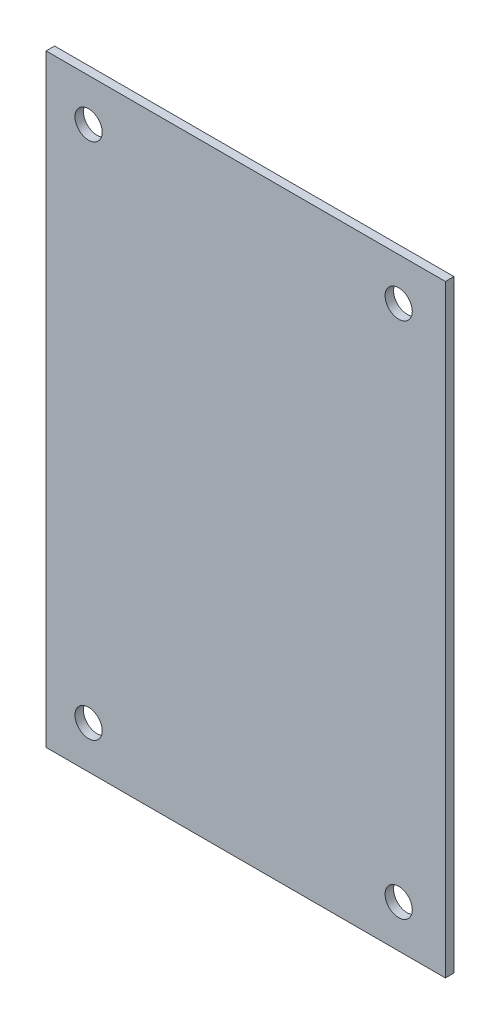
SolidWorks part; units mm, degrees
ref_plane "正面" through (0, 0, 0) normal (0, 0, 1) x (1, 0, 0)
ref_plane "平面" through (0, 0, 0) normal (0, 1, 0) x (1, 0, 0)
ref_plane "右側面" through (0, 0, 0) normal (1, 0, 0) x (0, 0, -1)
sketch "ｽｹｯﾁ1" plane through (0, 0, 0) normal (0, 0, 1) x (1, 0, 0)
  line L1 (-23.5, 35.5) -> (23.5, 35.5)
  line L2 (-23.5, 35.5) -> (-23.5, -35.5)
  line L3 (-23.5, -35.5) -> (23.5, -35.5)
  line L4 (23.5, 35.5) -> (23.5, -35.5)
  dimension "D1" = 47
  dimension "D2" = 71
  dimension "D3" = 35.5
  dimension "D4" = 23.5
extrude "ﾎﾞｽ - 押し出し1" add sketch "ｽｹｯﾁ1" along normal blind 1
sketch "ｽｹｯﾁ2" plane through (0, 0, 1) normal (0, 0, 1) x (1, 0, 0)
  line L0 (-23.5, -35.5) -> (23.5, -35.5) construction
  line L1 (-23.5, 35.5) -> (-23.5, -35.5) construction
  circle A0 centre (-18.5, -30.5) radius 1.6
  dimension "D1" = 3.2
  dimension "D2" = 5
  dimension "D3" = 5
extrude "ｶｯﾄ - 押し出し1" cut sketch "ｽｹｯﾁ2" against normal blind 1
pattern_linear "直線ﾊﾟﾀｰﾝ1" count 2 spacing 36.5 along (1, 0, 0) count 2 spacing 61 along (0, 1, 0) of "ｶｯﾄ - 押し出し1"
